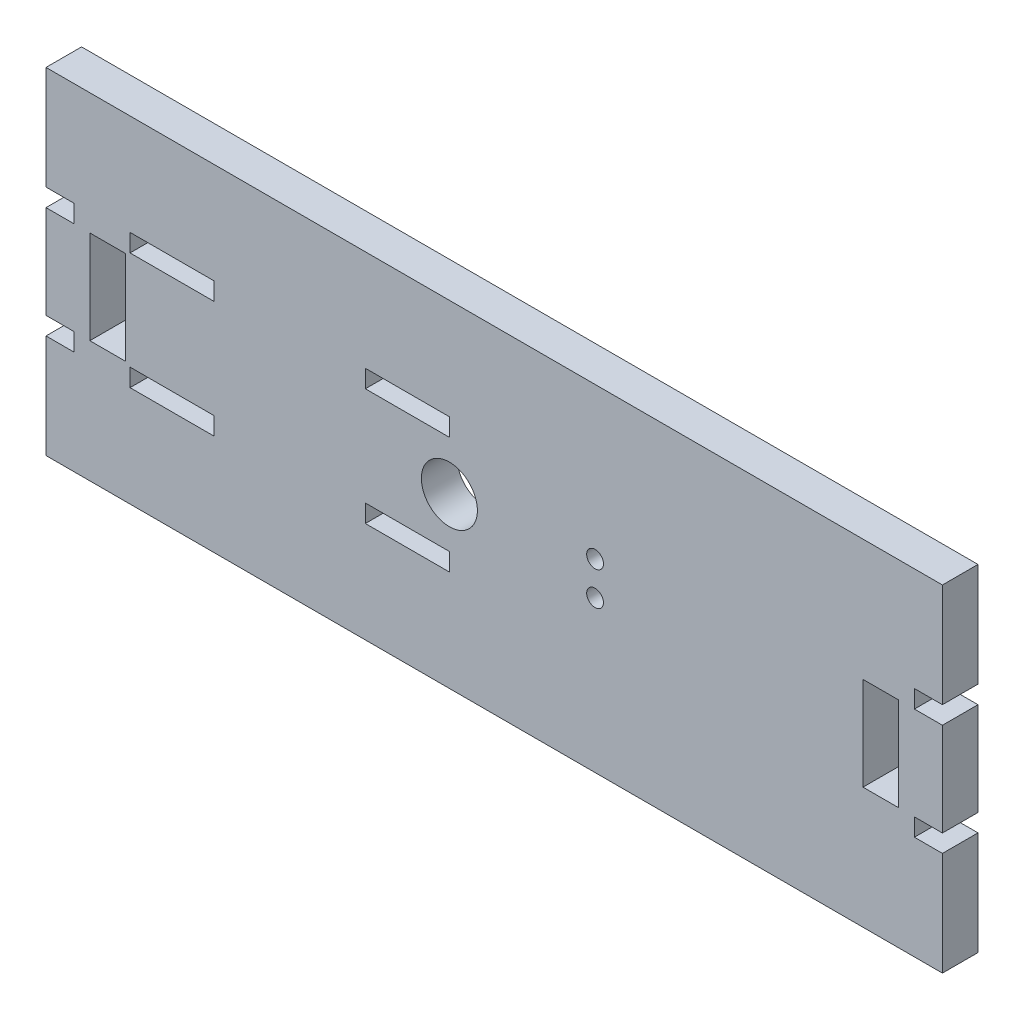
SolidWorks part; units mm, degrees
ref_plane "Front Plane" through (0, 0, 0) normal (0, 0, 1) x (1, 0, 0)
ref_plane "Top Plane" through (0, 0, 0) normal (0, 1, 0) x (1, 0, 0)
ref_plane "Right Plane" through (0, 0, 0) normal (1, 0, 0) x (0, 0, -1)
sketch "Sketch1" plane through (0, 0, 0) normal (0, 0, 1) x (1, 0, 0)
  line L0 (160, 0) -> (160, 18.5075)
  line L1 (0, 0) -> (160, 0)
  line L3 (0, 60) -> (160, 60)
  line L5 (0, 0) -> (0, 18.495)
  line L6 (0, 21.67) -> (0, 38.33)
  line L7 (7.825, 38.33) -> (5, 38.33) construction
  line L8 (5, 38.33) -> (7.825, 38.33) construction
  line L9 (155, 38.3175) -> (152.175, 38.3175) construction
  line L10 (72, 60) -> (72, 0) construction
  line L11 (72, 30) -> (98, 30) construction
  line L12 (72, 18) -> (57, 18)
  line L13 (72, 18) -> (72, 21.175)
  line L14 (72, 21.175) -> (57, 21.175)
  line L15 (57, 18) -> (57, 21.175)
  line L16 (72, 38.825) -> (57, 38.825)
  line L17 (72, 38.825) -> (72, 42)
  line L18 (72, 42) -> (57, 42)
  line L19 (57, 38.825) -> (57, 42)
  line L20 (98, 30) -> (98, 27) construction
  line L21 (98, 30) -> (98, 33) construction
  line L23 (30, 42) -> (15, 42)
  line L24 (0, 41.505) -> (5, 41.505)
  line L25 (5, 41.505) -> (5, 38.33)
  line L26 (5, 38.33) -> (0, 38.33)
  line L27 (5, 18.495) -> (0, 18.495)
  line L28 (5, 21.67) -> (5, 18.495)
  line L29 (0, 21.67) -> (5, 21.67)
  line L30 (7.825, 38.33) -> (7.825, 21.67)
  line L31 (7.825, 21.67) -> (14.175, 21.67)
  line L32 (14.175, 21.67) -> (14.175, 38.33)
  line L33 (14.175, 38.33) -> (7.825, 38.33)
  line L34 (155, 41.4925) -> (160, 41.4925)
  line L35 (155, 38.3175) -> (155, 41.4925)
  line L36 (160, 38.3175) -> (155, 38.3175)
  line L37 (155, 21.6575) -> (160, 21.6575)
  line L38 (160, 18.5075) -> (155, 18.5075)
  line L39 (155, 18.5075) -> (155, 21.6575)
  line L40 (145.825, 21.6575) -> (152.175, 21.6575)
  line L41 (145.825, 38.3175) -> (145.825, 21.6575)
  line L42 (152.175, 38.3175) -> (145.825, 38.3175)
  line L43 (152.175, 21.6575) -> (152.175, 38.3175)
  line L44 (0, 41.505) -> (0, 60)
  line L46 (160, 41.4925) -> (160, 60)
  line L47 (160, 21.6575) -> (160, 38.3175)
  line L48 (30, 42) -> (30, 38.825)
  line L49 (30, 38.825) -> (15, 38.825)
  line L50 (15, 42) -> (15, 38.825)
  line L51 (30, 21.175) -> (15, 21.175)
  line L52 (30, 21.175) -> (30, 18)
  line L53 (30, 18) -> (15, 18)
  line L54 (15, 21.175) -> (15, 18)
  circle A0 centre (72, 30) radius 5
  circle A1 centre (98, 27) radius 1.5
  circle A2 centre (98, 33) radius 1.5
  point P57 (80, 0)
  dimension "D16" = 10
  dimension "D26" = 3
  dimension "D27" = 3
  dimension "D1" = 160
  dimension "D2" = 16.66
  dimension "D3" = 6.35
  dimension "D4" = 3.175
  dimension "D5" = 16.66
  dimension "D6" = 3.15
  dimension "D7" = 16.66
  dimension "D8" = 6.35
  dimension "D9" = 3.175
  dimension "D10" = 3.175
  dimension "D11" = 5
  dimension "D12" = 5
  dimension "D13" = 16.66
  dimension "D14" = 60
  dimension "D15" = 131.65
  dimension "D17" = 3.175
  dimension "D18" = 3.175
  dimension "D19" = 15
  dimension "D20" = 15
  dimension "D21" = 18
  dimension "D22" = 18
  dimension "D23" = 26
  dimension "D24" = 3
  dimension "D25" = 3
  dimension "D28" = 3.175
  dimension "D29" = 15
  dimension "D30" = 15
  dimension "D31" = 3.175
  dimension "D32" = 15
  dimension "D33" = 8
extrude "Boss-Extrude1" add sketch "Sketch1" along normal blind 6.35
